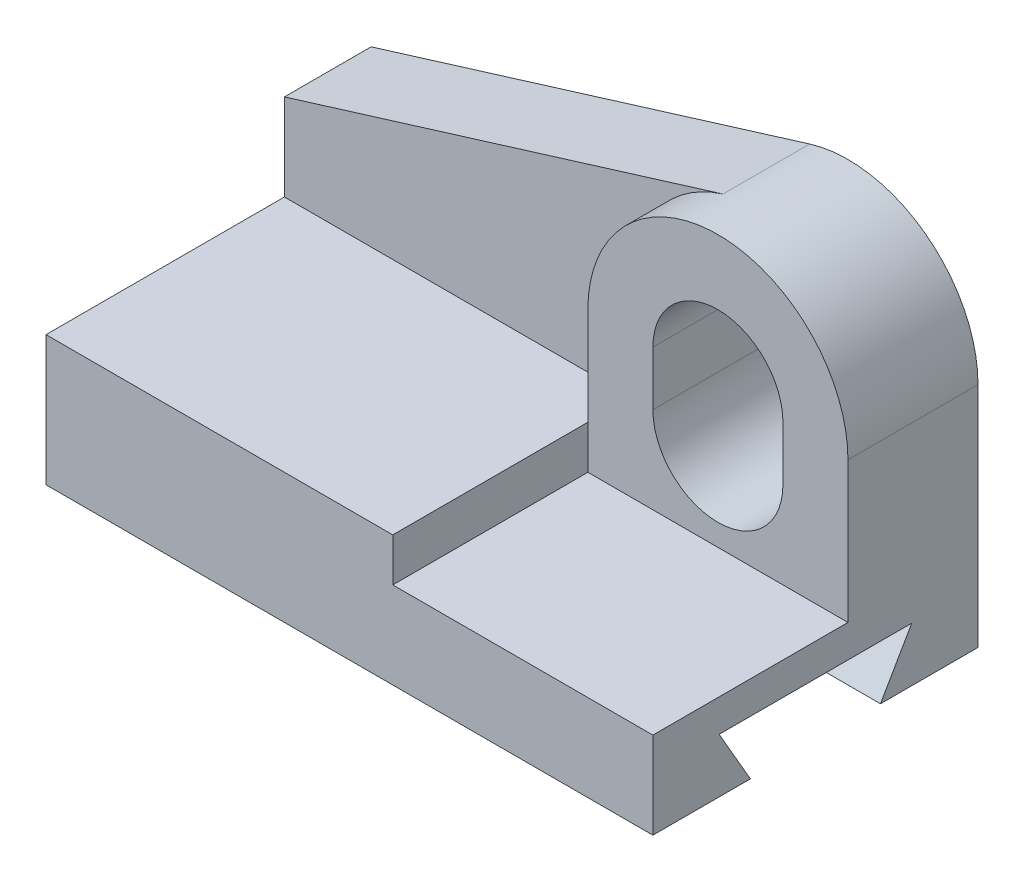
SolidWorks part; units mm, degrees
ref_plane "前视基准面" through (0, 0, 0) normal (0, 0, 1) x (1, 0, 0)
ref_plane "上视基准面" through (0, 0, 0) normal (0, 1, 0) x (1, 0, 0)
ref_plane "右视基准面" through (0, 0, 0) normal (1, 0, 0) x (0, 0, -1)
other "Configuration Table"
sketch "草图1" plane through (0, 0, 0) normal (0, 1, 0) x (1, 0, 0)
  line L1 (-28, 15) -> (28, 15)
  line L2 (-28, 15) -> (-28, -15)
  line L3 (-28, -15) -> (28, -15)
  line L4 (28, 15) -> (28, -15)
  line L5 (-28, 15) -> (28, -15) construction
  line L6 (-28, -15) -> (28, 15) construction
  point P0 (0, 0)
  point P6 (28, 3)
  dimension "D1" = 56
  dimension "D2" = 30
  dimension "D3" = 18
extrude "凸台-拉伸1" add sketch "草图1" along normal blind 12 contours L2 L1 L4 L3
sketch "草图2" plane through (-28, 0, 0) normal (-1, 0, 0) x (0, 0, 1)
  line L6 (-6, 0) -> (6, 0)
  line L7 (-15, 0) -> (15, 0) construction
  line L8 (6, 0) -> (8.8868, 5)
  line L9 (8.8868, 5) -> (-8.8868, 5)
  line L10 (-8.8868, 5) -> (-6, 0)
  point P6 (0, 0)
  dimension "D1" = 12
  dimension "D2" = 60
  dimension "D3" = 60
  dimension "D4" = 5
extrude "切除-拉伸1" cut sketch "草图2" against normal through all
sketch "草图3" plane through (0, 12, 0) normal (0, 1, 0) x (1, 0, 0)
  line L0 (28, 15) -> (28, -15) construction
  line L7 (-28, -15) -> (28, -15) construction
  line L8 (28, 7) -> (4, 7)
  line L9 (28, 7) -> (28, -15)
  line L10 (28, -15) -> (4, -15)
  line L11 (4, 7) -> (4, -15)
  point P0 (28, 7)
  dimension "D1" = 22
  dimension "D2" = 24
extrude "切除-拉伸3" cut sketch "草图3" against normal blind 4
sketch "草图4" plane through (0, 12, 0) normal (0, 1, 0) x (1, 0, 0)
  line L1 (-28, 15) -> (28, 15)
  line L2 (-28, 15) -> (-28, 7)
  line L3 (-28, 7) -> (28, 7)
  line L4 (28, 15) -> (28, 7)
extrude "凸台-拉伸2" add sketch "草图4" along normal blind 25
sketch "草图5" plane through (0, 0, -7) normal (0, 0, 1) x (1, 0, 0)
  line L1 (-28, 37) -> (-28, 12) construction
  line L4 (28, 8) -> (28, 37) construction
  line L6 (16, 8) -> (16, 41.075) construction
  line L7 (-28, 20) -> (12.4666, 32.468)
  line L21 (28, 8) -> (28, 37)
  line L22 (28, 37) -> (-28, 37)
  line L23 (-28, 37) -> (-28, 12)
  line L24 (-28, 12) -> (4, 12)
  line L25 (4, 12) -> (4, 8)
  line L26 (4, 8) -> (28, 8)
  line L27 (28, 8) -> (28, 37)
  line L28 (28, 37) -> (-28, 37)
  line L29 (-28, 37) -> (-28, 12)
  line L30 (-28, 12) -> (4, 12)
  line L31 (4, 12) -> (4, 8)
  line L32 (4, 8) -> (28, 8)
  arc A2 (12.4666, 32.468) -> (28, 21) centre (16, 21) cw
  point P5 (16, 8)
  line M11 (28, 37) -> (-28, 37)
  line M12 (-28, 37) -> (-28, 12)
  dimension "D3" = 13
  dimension "D2" = 8
  dimension "D1" = 0
extrude "切除-拉伸5" cut sketch "草图5" against normal blind 25 contours L6 A2 L27 M11 | A2 L6 L28 L7 M12
sketch "草图6" plane through (0, 0, -7) normal (0, 0, 1) x (1, 0, 0)
  line L0 (16, 8) -> (16, 40.1247) construction
  line L1 (4, 8) -> (4, 21)
  line L2 (16, 21) -> (16, 16) construction
  line L3 (22, 21) -> (22, 16)
  line L4 (10, 21) -> (10, 16)
  line L6 (28, 8) -> (28, 21)
  line L7 (12.4666, 32.468) -> (-28, 20)
  line L8 (-28, 20) -> (-28, 12)
  line L9 (-28, 12) -> (4, 12)
  line L10 (4, 12) -> (4, 8)
  line L11 (4, 8) -> (28, 8)
  line L12 (28, 8) -> (28, 21)
  line L13 (12.4666, 32.468) -> (-28, 20)
  line L14 (-28, 20) -> (-28, 12)
  line L15 (-28, 12) -> (4, 12)
  line L16 (4, 12) -> (4, 8)
  line L17 (4, 8) -> (28, 8)
  arc A0 (28, 21) -> (4.004, 20.6905) centre (16, 21) ccw
  arc A1 (28, 21) -> (12.4666, 32.468) centre (16, 21) ccw
  arc A2 (28, 21) -> (12.4666, 32.468) centre (16, 21) ccw
  arc A3 (22, 21) -> (10, 21) centre (16, 21) ccw
  arc A4 (10, 16) -> (22, 16) centre (16, 16) ccw
  point P14 (16, 18.5)
  dimension "D4" = 6
  dimension "D2" = 8
  dimension "D3" = 5
  dimension "D1" = 0
extrude "切除-拉伸6" cut sketch "草图6" against normal through all contours L4 A4 L3 A3
sketch "草图7" plane through (0, 0, -7) normal (0, 0, 1) x (1, 0, 0)
  line L0 (4, 8) -> (4, 21)
  line L6 (28, 8) -> (28, 21)
  line L7 (12.4666, 32.468) -> (-28, 20)
  line L8 (-28, 20) -> (-28, 12)
  line L9 (-28, 12) -> (4, 12)
  line L10 (4, 12) -> (4, 8)
  line L11 (4, 8) -> (28, 8)
  line L12 (28, 8) -> (28, 21)
  line L13 (12.4666, 32.468) -> (-28, 20)
  line L14 (-28, 20) -> (-28, 12)
  line L15 (-28, 12) -> (4, 12)
  line L16 (4, 12) -> (4, 8)
  line L17 (4, 8) -> (28, 8)
  arc A0 (28, 21) -> (4, 21) centre (16, 21) ccw
  arc A1 (28, 21) -> (12.4666, 32.468) centre (16, 21) ccw
  arc A2 (28, 21) -> (12.4666, 32.468) centre (16, 21) ccw
  arc M10 (22, 16) -> (10, 16) centre (16, 16) cw
  line M11 (10, 16) -> (10, 21)
  arc M12 (10, 21) -> (22, 21) centre (16, 21) cw
  line M13 (22, 21) -> (22, 16)
  line M14 (28, 8) -> (28, 21)
  arc M15 (28, 21) -> (12.4666, 32.468) centre (16, 21) ccw
  line M19 (4, 12) -> (4, 8)
  line M20 (4, 8) -> (28, 8)
  dimension "D1" = 0
extrude "凸台-拉伸3" add sketch "草图7" along normal blind 4 contours A0 L0 M15 M19 M20 M14 M13 M10 M11 M12
